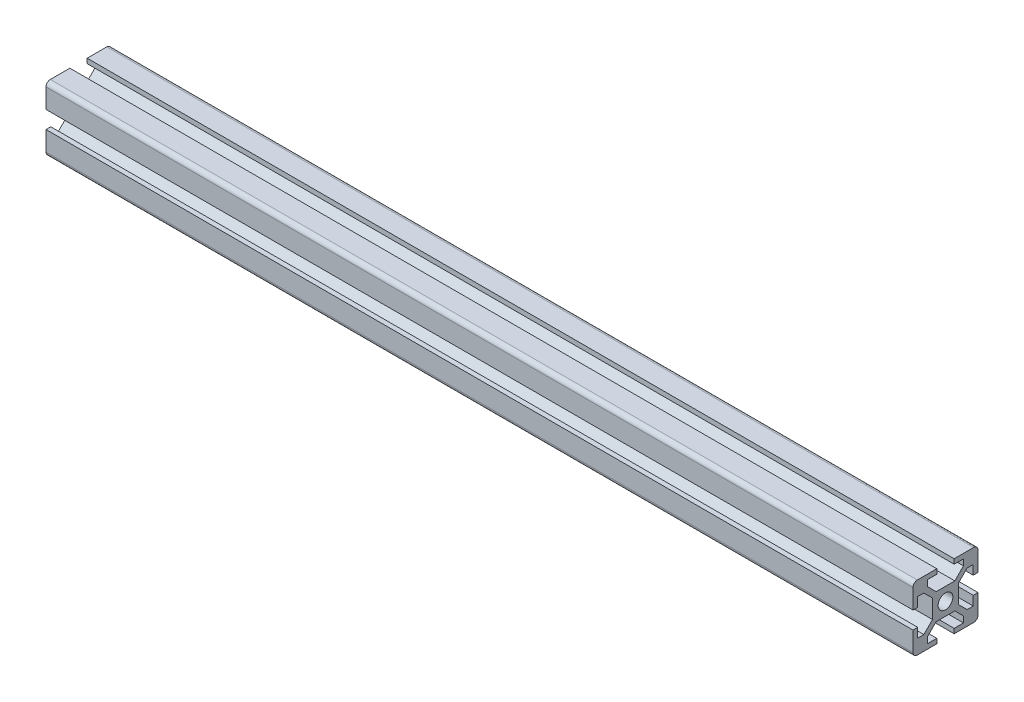
SolidWorks part; units mm, degrees
ref_plane "Front Plane" through (0, 0, 0) normal (0, 0, 1) x (1, 0, 0)
ref_plane "Top Plane" through (0, 0, 0) normal (0, 1, 0) x (1, 0, 0)
ref_plane "Right Plane" through (0, 0, 0) normal (1, 0, 0) x (0, 0, -1)
sketch "Sketch1" plane through (0, 0, 0) normal (0, 1, 0) x (1, 0, 0)
  line L0 (0, 0) -> (400, 0)
  dimension "D1" = 400
other "Aluminium extrusion 3030(1)"
ref_plane "Plane1" through (0, 0, 0) normal (1, 0, 0) x (0, 0, -1)
sketch "Sketch17" plane through (0, 0, 0) normal (1, 0, 0) x (0, 0, -1)
  line L0 (0, 0) -> (-21.5122, 0) construction
  line L1 (0, 0) -> (0, 25.7819) construction
  line L2 (0, 6) -> (-4.3029, 6)
  line L3 (-4.3029, 6) -> (-8.3, 9.9971)
  line L4 (-8.3, 12.8) -> (-4, 12.8)
  line L5 (-8.3, 9.9971) -> (-8.3, 12.8)
  line L6 (-4, 12.8) -> (-4, 15)
  line L7 (-4, 15) -> (-13, 15)
  line L8 (-14.4142, 14.4142) -> (0, 0) construction
  line L9 (-6, 0) -> (-6, 4.3029)
  line L10 (-6, 4.3029) -> (-9.9971, 8.3)
  line L11 (-9.9971, 8.3) -> (-12.8, 8.3)
  line L12 (-12.8, 8.3) -> (-12.8, 4)
  line L13 (-12.8, 4) -> (-15, 4)
  line L14 (-15, 4) -> (-15, 13)
  line L15 (6, 0) -> (6, 4.3029)
  line L16 (6, 4.3029) -> (9.9971, 8.3)
  line L17 (9.9971, 8.3) -> (12.8, 8.3)
  line L18 (12.8, 8.3) -> (12.8, 4)
  line L19 (12.8, 4) -> (15, 4)
  line L20 (15, 4) -> (15, 13)
  line L21 (4, 15) -> (13, 15)
  line L22 (4, 12.8) -> (4, 15)
  line L23 (8.3, 12.8) -> (4, 12.8)
  line L24 (8.3, 9.9971) -> (8.3, 12.8)
  line L25 (4.3029, 6) -> (8.3, 9.9971)
  line L26 (0, 6) -> (4.3029, 6)
  line L27 (0, -6) -> (4.3029, -6)
  line L28 (4.3029, -6) -> (8.3, -9.9971)
  line L29 (8.3, -9.9971) -> (8.3, -12.8)
  line L30 (8.3, -12.8) -> (4, -12.8)
  line L31 (4, -12.8) -> (4, -15)
  line L32 (4, -15) -> (13, -15)
  line L33 (15, -4) -> (15, -13)
  line L34 (12.8, -4) -> (15, -4)
  line L35 (12.8, -8.3) -> (12.8, -4)
  line L36 (9.9971, -8.3) -> (12.8, -8.3)
  line L37 (6, -4.3029) -> (9.9971, -8.3)
  line L38 (6, 0) -> (6, -4.3029)
  line L39 (-6, 0) -> (-6, -4.3029)
  line L40 (-6, -4.3029) -> (-9.9971, -8.3)
  line L41 (-9.9971, -8.3) -> (-12.8, -8.3)
  line L42 (-12.8, -8.3) -> (-12.8, -4)
  line L43 (-12.8, -4) -> (-15, -4)
  line L44 (-15, -4) -> (-15, -13)
  line L45 (-4, -15) -> (-13, -15)
  line L46 (-4, -12.8) -> (-4, -15)
  line L47 (-8.3, -12.8) -> (-4, -12.8)
  line L48 (-8.3, -9.9971) -> (-8.3, -12.8)
  line L49 (-4.3029, -6) -> (-8.3, -9.9971)
  line L50 (0, -6) -> (-4.3029, -6)
  circle A0 centre (0, 0) radius 3.4
  arc A1 (-13, 15) -> (-15, 13) centre (-13, 13) ccw
  arc A2 (15, 13) -> (13, 15) centre (13, 13) ccw
  arc A3 (13, -15) -> (15, -13) centre (13, -13) ccw
  arc A4 (-15, -13) -> (-13, -15) centre (-13, -13) ccw
  point P0 (0, 0)
  point P3 (0, 0)
  point P70 (0, 0)
  dimension "D1" = 6.8
  dimension "D7" = 1.2
  dimension "D8" = 2
  dimension "D2" = 45
  dimension "D3" = 15
  dimension "D4" = 9
  dimension "D5" = 8.3
  dimension "D6" = 4
  dimension "D9" = 2.2
